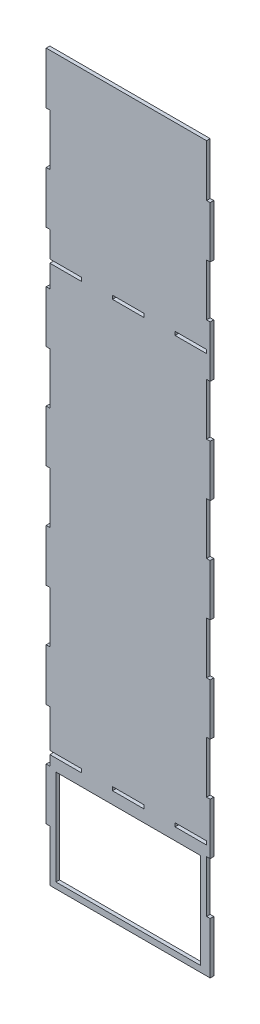
SolidWorks part; units mm, degrees
ref_plane "Front Plane" through (0, 0, 0) normal (0, 0, 1) x (1, 0, 0)
ref_plane "Top Plane" through (0, 0, 0) normal (0, 1, 0) x (1, 0, 0)
ref_plane "Right Plane" through (0, 0, 0) normal (1, 0, 0) x (0, 0, -1)
sketch "Sketch1" plane through (0, 0, 0) normal (0, 0, 1) x (1, 0, 0)
  line L0 (-67.9978, 0) -> (65, 0)
  line L1 (65, 0) -> (65, -43.0071)
  line L2 (65, -43.0071) -> (67.9978, -43.0071)
  line L3 (67.9978, -43.0071) -> (67.9978, -85.7143)
  line L4 (67.9978, -85.7143) -> (65, -85.7143)
  line L5 (65, -85.7143) -> (65, -128.7214)
  line L6 (65, -128.7214) -> (67.9978, -128.7214)
  line L7 (67.9978, -128.7214) -> (67.9978, -171.4286)
  line L8 (67.9978, -171.4286) -> (65, -171.4286)
  line L9 (65, -171.4286) -> (65, -214.4357)
  line L10 (65, -214.4357) -> (67.9978, -214.4357)
  line L11 (67.9978, -214.4357) -> (67.9978, -257.1429)
  line L12 (67.9978, -257.1429) -> (65, -257.1429)
  line L13 (65, -257.1429) -> (65, -300.15)
  line L14 (65, -300.15) -> (67.9978, -300.15)
  line L15 (67.9978, -300.15) -> (67.9978, -342.8571)
  line L16 (67.9978, -342.8571) -> (65, -342.8571)
  line L17 (65, -342.8571) -> (65, -385.8643)
  line L18 (65, -385.8643) -> (67.9978, -385.8643)
  line L19 (67.9978, -385.8643) -> (67.9978, -428.5714)
  line L20 (67.9978, -428.5714) -> (65, -428.5714)
  line L21 (65, -428.5714) -> (65, -471.5786)
  line L22 (65, -471.5786) -> (67.9978, -471.5786)
  line L23 (67.9978, -471.5786) -> (67.9978, -514.2857)
  line L24 (67.9978, -514.2857) -> (65, -514.2857)
  line L25 (65, -514.2857) -> (65, -557.2929)
  line L26 (65, -557.2929) -> (67.9978, -557.2929)
  line L27 (67.9978, -557.2929) -> (67.9978, -600)
  line L28 (67.9978, -600) -> (-65, -600)
  line L30 (-67.9978, -514.2857) -> (-65, -514.2857)
  line L31 (-65, -514.2857) -> (-65, -471.5786)
  line L32 (-65, -471.5786) -> (-67.9978, -471.5786)
  line L33 (-67.9978, -471.5786) -> (-67.9978, -428.5714)
  line L34 (-67.9978, -428.5714) -> (-65, -428.5714)
  line L35 (-65, -428.5714) -> (-65, -385.8643)
  line L36 (-65, -385.8643) -> (-67.9978, -385.8643)
  line L37 (-67.9978, -385.8643) -> (-67.9978, -342.8571)
  line L38 (-67.9978, -342.8571) -> (-65, -342.8571)
  line L39 (-65, -342.8571) -> (-65, -300.15)
  line L40 (-65, -300.15) -> (-67.9978, -300.15)
  line L41 (-67.9978, -300.15) -> (-67.9978, -257.1429)
  line L42 (-67.9978, -257.1429) -> (-65, -257.1429)
  line L43 (-65, -257.1429) -> (-65, -214.4357)
  line L44 (-65, -214.4357) -> (-67.9978, -214.4357)
  line L45 (-67.9978, -214.4357) -> (-67.9978, -171.4286)
  line L46 (-67.9978, -171.4286) -> (-65, -171.4286)
  line L47 (-65, -171.4286) -> (-65, -128.7214)
  line L48 (-65, -128.7214) -> (-67.9978, -128.7214)
  line L49 (-67.9978, -128.7214) -> (-67.9978, -85.7143)
  line L50 (-67.9978, -85.7143) -> (-65, -85.7143)
  line L51 (-65, -85.7143) -> (-65, -43.0071)
  line L52 (-65, -43.0071) -> (-67.9978, -43.0071)
  line L53 (-67.9978, -43.0071) -> (-67.9978, 0)
  line L56 (-67.9978, -514.2857) -> (-67.9978, -557.2929)
  line L57 (-67.9978, -557.2929) -> (-65, -557.2929)
  line L58 (-38.88, -151.5) -> (-13.06, -151.5) construction
  line L59 (-60, -595) -> (60, -595)
  line L60 (-60, -595) -> (-60, -516)
  line L61 (-60, -516) -> (60, -516)
  line L62 (60, -595) -> (60, -516)
  line L63 (-60, -595) -> (60, -516) construction
  line L64 (-60, -516) -> (60, -595) construction
  line L69 (-65, -153) -> (-38.88, -153)
  line L70 (-65, -153) -> (-65, -150)
  line L75 (-65, -150) -> (-38.88, -150)
  line L76 (-38.88, -153) -> (-38.88, -150)
  line L77 (-13.06, -153) -> (13.06, -153)
  line L78 (-13.06, -153) -> (-13.06, -150)
  line L79 (-13.06, -150) -> (13.06, -150)
  line L80 (13.06, -153) -> (13.06, -150)
  line L89 (38.88, -153) -> (65, -153)
  line L90 (38.88, -153) -> (38.88, -150)
  line L91 (38.88, -150) -> (65, -150)
  line L92 (65, -153) -> (65, -150)
  line L93 (13.06, -151.5) -> (38.88, -151.5) construction
  line L94 (-65, -151.5) -> (-39.18, -151.5) construction
  line L95 (-39.18, -151.5) -> (-38.88, -151.5) construction
  line L96 (-65, -506) -> (-65, -503)
  line L97 (-65, -506) -> (-38.88, -506)
  line L98 (-38.88, -506) -> (-38.88, -503)
  line L99 (-65, -503) -> (-38.88, -503)
  line L100 (-13.06, -506) -> (-13.06, -503)
  line L101 (-13.06, -506) -> (13.06, -506)
  line L102 (13.06, -506) -> (13.06, -503)
  line L103 (-13.06, -503) -> (13.06, -503)
  line L104 (38.88, -506) -> (38.88, -503)
  line L105 (38.88, -506) -> (65, -506)
  line L106 (65, -506) -> (65, -503)
  line L107 (38.88, -503) -> (65, -503)
  line L108 (-65, -557.2929) -> (-65, -600)
  line L109 (-65, -43.0071) -> (-65, -0.3) construction
  line L110 (-65, -0.3) -> (-65, 0) construction
  point P0 (0, -555.5)
  point P63 (0, -150)
  point P79 (-65, -64.3607)
  dimension "500" = 600
  dimension "D3" = 2.9978
  dimension "D4" = 5
  dimension "D5" = 0.3
  dimension "D6" = 0.3
  dimension "D7" = 3
  dimension "D9" = 2
  dimension "D10" = 350
  dimension "D11" = 10
  dimension "D12" = 5
  dimension "D8" = 150
  dimension "D13" = 130
extrude "Boss-Extrude1" add sketch "Sketch1" along normal blind 3
